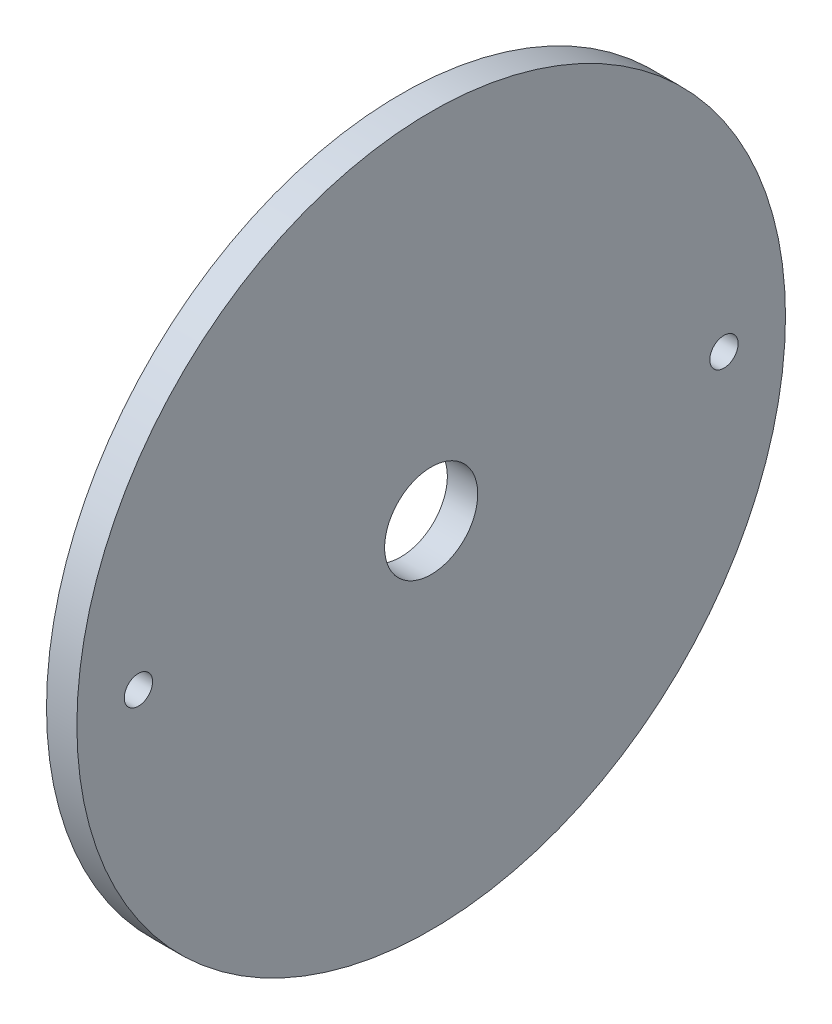
SolidWorks part; units mm, degrees
ref_plane "Front Plane" through (0, 0, 0) normal (0, 0, 1) x (1, 0, 0)
ref_plane "Top Plane" through (0, 0, 0) normal (0, 1, 0) x (1, 0, 0)
ref_plane "Right Plane" through (0, 0, 0) normal (1, 0, 0) x (0, 0, -1)
sketch "Sketch1" plane through (0, 0, 0) normal (1, 0, 0) x (0, 0, -1)
  circle A0 centre (0, 0) radius 2.3
  circle A1 centre (0, 0) radius 17.5
  circle A2 centre (14.46, 0) radius 0.7
  circle A3 centre (-14.46, 0) radius 0.7
  point P8 (0, 0)
  dimension "D1" = 4.6
  dimension "D2" = 35
  dimension "D3" = 14.46
  dimension "D4" = 14.46
  dimension "D5" = 1.4
  dimension "D6" = 1.4
extrude "Boss-Extrude1" add sketch "Sketch1" along normal blind 1.5
